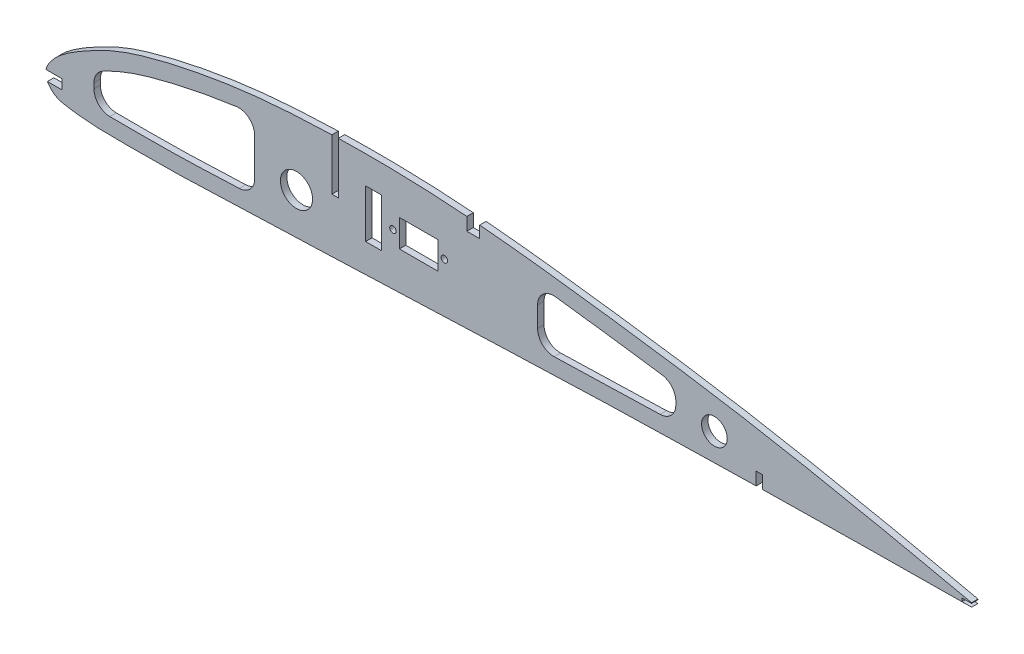
SolidWorks part; units mm, degrees
material "轻木"
ref_plane "前视基准面" through (0, 0, 0) normal (0, 0, 1) x (1, 0, 0)
ref_plane "上视基准面" through (0, 0, 0) normal (0, 1, 0) x (1, 0, 0)
ref_plane "右视基准面" through (0, 0, 0) normal (1, 0, 0) x (0, 0, -1)
other "Configuration Table"
curve "曲线1"
  spline degree 3 poles (300, 0.375, 0) (299.2857, 0.5355, 0) (297.8572, 0.8566, 0) (295.7147, 1.3378, 0) (293.5725, 1.8185, 0) (291.4302, 2.2982, 0) (289.2875, 2.7769, 0) (287.1442, 3.2543, 0) (285.001, 3.7299, 0) (282.8583, 4.2033, 0) (280.7163, 4.6744, 0) (278.5743, 5.1433, 0) (276.432, 5.6099, 0) (274.2889, 6.0741, 0) (272.145, 6.5358, 0) (269.2891, 7.1472, 0) (265.721, 7.9038, 0) (261.4399, 8.8, 0) (257.1573, 9.6847, 0) (252.8725, 10.5577, 0) (248.585, 11.4191, 0) (244.2942, 12.2686, 0) (240.0067, 13.1048, 0) (235.7231, 13.9276, 0) (231.4437, 14.735, 0) (227.1623, 15.5265, 0) (222.8779, 16.3002, 0) (218.5899, 17.0545, 0) (214.2976, 17.7876, 0) (210.0082, 18.4964, 0) (205.7223, 19.1793, 0) (201.441, 19.8388, 0) (197.1575, 20.4787, 0) (192.8717, 21.1016, 0) (188.5834, 21.71, 0) (184.2928, 22.3067, 0) (180.0042, 22.8936, 0) (175.7188, 23.4732, 0) (171.4371, 24.0431, 0) (167.1545, 24.6013, 0) (162.8704, 25.1452, 0) (158.5838, 25.6724, 0) (154.2938, 26.1804, 0) (150.0066, 26.6658, 0) (145.7226, 27.1265, 0) (141.4425, 27.5584, 0) (137.1601, 27.958, 0) (132.875, 28.3213, 0) (128.5869, 28.6439, 0) (124.2953, 28.9218, 0) (120.0053, 29.1506, 0) (115.7177, 29.3264, 0) (111.4337, 29.4514, 0) (107.1488, 29.5275, 0) (102.863, 29.5565, 0) (98.5762, 29.5401, 0) (94.2882, 29.4801, 0) (89.9957, 29.378, 0) (85.6999, 29.236, 0) (81.4026, 29.047, 0) (77.1093, 28.8043, 0) (72.8211, 28.5008, 0) (68.5389, 28.1296, 0) (64.264, 27.6835, 0) (60.7007, 27.2426, 0) (57.8461, 26.8442, 0) (55.696, 26.5216, 0) (53.5496, 26.1773, 0) (51.4067, 25.8115, 0) (49.2673, 25.4247, 0) (47.1314, 25.0171, 0) (44.9882, 24.5868, 0) (42.838, 24.1341, 0) (40.6818, 23.6568, 0) (38.5315, 23.1552, 0) (36.3875, 22.6273, 0) (34.2503, 22.0712, 0) (32.1202, 21.4847, 0) (30.3423, 20.9664, 0) (28.9132, 20.5311, 0) (27.8303, 20.1897, 0) (26.7518, 19.8362, 0) (25.6784, 19.4687, 0) (24.6112, 19.0858, 0) (23.551, 18.6856, 0) (22.4821, 18.2598, 0) (21.4059, 17.8057, 0) (20.3222, 17.3242, 0) (19.2465, 16.8243, 0) (18.1774, 16.3076, 0) (17.1139, 15.7762, 0) (16.0546, 15.2317, 0) (14.9819, 14.6674, 0) (13.8954, 14.0851, 0) (12.7977, 13.4827, 0) (11.7087, 12.8677, 0) (10.6313, 12.2387, 0) (9.5687, 11.5942, 0) (8.5237, 10.9329, 0) (7.6518, 10.3543, 0) (6.9458, 9.8665, 0) (6.3985, 9.4746, 0) (5.8573, 9.0705, 0) (5.3218, 8.651, 0) (4.7913, 8.2128, 0) (4.2653, 7.7527, 0) (3.6165, 7.1497, 0) (2.8604, 6.3846, 0) (2.0362, 5.4343, 0) (1.2959, 4.4252, 0) (0.6772, 3.3675, 0) (0.2189, 2.2697, 0) (-0.0383, 1.1392, 0) (-0.0456, 0.0749, 0) (0.1619, -0.885, 0) (0.4986, -1.7375, 0) (0.9635, -2.5517, 0) (1.5376, -3.3119, 0) (2.2026, -4.0019, 0) (2.94, -4.6051, 0) (3.6355, -5.044, 0) (4.2555, -5.3464, 0) (4.779, -5.5548, 0) (5.3118, -5.728, 0) (5.8521, -5.8723, 0) (6.398, -5.9938, 0) (6.9478, -6.0987, 0) (7.671, -6.2224, 0) (8.5669, -6.3647, 0) (9.636, -6.5177, 0) (10.7063, -6.6545, 0) (11.7778, -6.7754, 0) (12.8506, -6.8809, 0) (13.9246, -6.9713, 0) (14.9978, -7.047, 0) (16.0697, -7.1082, 0) (17.1403, -7.1566, 0) (18.2115, -7.1941, 0) (19.2831, -7.2222, 0) (20.3552, -7.2427, 0) (21.4275, -7.2573, 0) (22.4998, -7.2676, 0) (23.5718, -7.2752, 0) (24.6434, -7.2803, 0) (25.7147, -7.2832, 0) (26.7859, -7.2843, 0) (27.8572, -7.2839, 0) (28.9285, -7.2822, 0) (30.3573, -7.2788, 0) (32.1433, -7.2727, 0) (34.2864, -7.2613, 0) (36.4292, -7.2444, 0) (38.5718, -7.2208, 0) (40.7144, -7.1891, 0) (42.8572, -7.148, 0) (45.0005, -7.0962, 0) (47.1439, -7.0325, 0) (49.2871, -6.9587, 0) (51.4297, -6.8772, 0) (53.572, -6.7902, 0) (55.7143, -6.6999, 0) (57.857, -6.6086, 0) (60.7142, -6.4884, 0) (64.2858, -6.3465, 0) (68.5714, -6.1868, 0) (72.8565, -6.0353, 0) (77.1416, -5.8893, 0) (81.427, -5.7463, 0) (85.7132, -5.6038, 0) (90.0001, -5.4593, 0) (94.287, -5.3101, 0) (98.5731, -5.1566, 0) (102.8583, -4.9992, 0) (107.1431, -4.8383, 0) (111.4281, -4.6742, 0) (115.7138, -4.5074, 0) (120.0001, -4.3383, 0) (124.2865, -4.1673, 0) (128.5722, -3.9953, 0) (132.8572, -3.8233, 0) (137.142, -3.6525, 0) (141.4271, -3.4838, 0) (145.7131, -3.3181, 0) (149.9996, -3.1567, 0) (154.286, -3.0004, 0) (158.5714, -2.8495, 0) (162.8564, -2.7043, 0) (167.1412, -2.5651, 0) (171.4266, -2.4321, 0) (175.7128, -2.3056, 0) (179.9996, -2.1858, 0) (184.2862, -2.0731, 0) (188.5719, -1.9664, 0) (192.857, -1.8646, 0) (197.1419, -1.7668, 0) (201.4272, -1.6719, 0) (205.7132, -1.5788, 0) (209.9999, -1.4865, 0) (214.2864, -1.3941, 0) (218.5722, -1.3027, 0) (222.8572, -1.2136, 0) (227.142, -1.128, 0) (231.4272, -1.0471, 0) (235.7132, -0.9723, 0) (239.9998, -0.9046, 0) (244.2864, -0.8454, 0) (248.5722, -0.7928, 0) (252.8573, -0.7451, 0) (257.1422, -0.7003, 0) (261.4274, -0.6568, 0) (265.7134, -0.6127, 0) (269.2855, -0.574, 0) (272.1433, -0.5408, 0) (274.2862, -0.5157, 0) (276.4287, -0.4908, 0) (278.5712, -0.4671, 0) (280.7137, -0.4452, 0) (282.8567, -0.4258, 0) (285, -0.4096, 0) (287.1432, -0.3973, 0) (289.2862, -0.3884, 0) (291.4287, -0.3824, 0) (293.5711, -0.3786, 0) (295.7137, -0.3765, 0) (297.8567, -0.3754, 0) (299.2855, -0.3751, 0) (300, -0.375, 0) knots 0 0 0 0 0.003574 0.007146 0.010718 0.01429 0.017862 0.021434 0.025008 0.028577 0.032145 0.035713 0.03928 0.042847 0.046415 0.049985 0.057103 0.064219 0.071333 0.078448 0.085563 0.092679 0.099797 0.106885 0.11397 0.121053 0.128137 0.13522 0.142305 0.149391 0.15644 0.163488 0.170534 0.17758 0.184627 0.191675 0.198725 0.205755 0.212782 0.219809 0.226834 0.233861 0.240889 0.24792 0.254921 0.26192 0.268917 0.275914 0.28291 0.289907 0.296905 0.303879 0.310852 0.317824 0.324796 0.331771 0.338748 0.345728 0.352728 0.359727 0.366723 0.373717 0.380709 0.387701 0.394695 0.398233 0.40177 0.405307 0.408843 0.41238 0.415918 0.419457 0.42305 0.426643 0.430235 0.433828 0.43742 0.441014 0.444611 0.446459 0.448306 0.450153 0.451999 0.453844 0.455687 0.45753 0.459459 0.461388 0.463318 0.465249 0.467183 0.469121 0.471062 0.4731 0.475138 0.477173 0.479204 0.481227 0.483239 0.48524 0.486334 0.487428 0.488525 0.48963 0.490748 0.491883 0.493041 0.495071 0.497131 0.499176 0.501171 0.503098 0.50496 0.506796 0.508242 0.509728 0.511253 0.512804 0.514366 0.515919 0.517444 0.518368 0.519283 0.520192 0.521101 0.522011 0.522922 0.523833 0.525592 0.527349 0.529104 0.530859 0.532612 0.534366 0.53612 0.537863 0.539607 0.54135 0.543094 0.544839 0.546584 0.548329 0.550073 0.551817 0.55356 0.555302 0.557045 0.558788 0.560532 0.564019 0.567506 0.570992 0.574478 0.577965 0.581452 0.584939 0.588429 0.591918 0.595406 0.598895 0.602383 0.605872 0.609363 0.616342 0.623319 0.630295 0.637271 0.644247 0.651224 0.658203 0.665183 0.672161 0.679137 0.686114 0.69309 0.700068 0.707048 0.714028 0.721006 0.727983 0.73496 0.741937 0.748915 0.755896 0.762874 0.769851 0.776826 0.783801 0.790777 0.797753 0.804732 0.811709 0.818683 0.825657 0.83263 0.839604 0.846578 0.853555 0.860532 0.867506 0.874479 0.881452 0.888424 0.895399 0.902375 0.90935 0.916324 0.923296 0.930267 0.937239 0.944213 0.951188 0.954676 0.958163 0.961649 0.965135 0.96862 0.972107 0.975595 0.979082 0.982569 0.986054 0.98954 0.993026 0.996512 1 1 1 1
curve "曲线2"
  spline degree 3 poles (299.6892, 0.0825, 0) (300.1498, -0.0478, 0) (299.7114, 0.1074, 0) (299.5104, 0.1872, 0) (299.2477, 0.2871, 0) (298.8504, 0.4413, 0) (298.294, 0.6613, 0) (297.5919, 0.9463, 0) (296.8903, 1.2362, 0) (296.0644, 1.581, 0) (295.1136, 1.9799, 0) (294.0373, 2.431, 0) (292.9597, 2.8788, 0) (291.7683, 3.3665, 0) (290.4608, 3.8877, 0) (289.0365, 4.4399, 0) (287.6073, 4.9796, 0) (286.0635, 5.5484, 0) (284.4048, 6.1444, 0) (282.6311, 6.7664, 0) (280.8534, 7.377, 0) (278.9651, 8.0149, 0) (276.9667, 8.6805, 0) (274.8582, 9.373, 0) (272.7471, 10.0574, 0) (270.5382, 10.7652, 0) (268.2318, 11.4959, 0) (265.8278, 12.2485, 0) (263.4214, 12.9932, 0) (260.9293, 13.7558, 0) (258.3517, 14.5354, 0) (255.6885, 15.3308, 0) (253.0225, 16.1168, 0) (250.2835, 16.9138, 0) (247.4714, 17.7205, 0) (244.5864, 18.536, 0) (241.6982, 19.3402, 0) (238.749, 20.1489, 0) (235.7391, 20.9612, 0) (232.6684, 21.7757, 0) (229.594, 22.5763, 0) (226.4711, 23.374, 0) (223.2997, 24.1675, 0) (220.08, 24.9553, 0) (216.8561, 25.726, 0) (213.5945, 26.4871, 0) (210.2953, 27.2373, 0) (206.9588, 27.975, 0) (203.6178, 28.6919, 0) (200.2497, 29.3918, 0) (196.8549, 30.0732, 0) (193.4336, 30.7349, 0) (190.0077, 31.3718, 0) (186.5618, 31.9862, 0) (183.0963, 32.577, 0) (179.6117, 33.1436, 0) (176.1229, 33.6833, 0) (172.6234, 34.197, 0) (169.1136, 34.6844, 0) (165.5943, 35.1447, 0) (162.0713, 35.5767, 0) (158.5465, 35.9798, 0) (155.0205, 36.3535, 0) (151.4939, 36.6979, 0) (147.9646, 37.0129, 0) (144.4431, 37.2978, 0) (140.9302, 37.5529, 0) (137.4264, 37.7777, 0) (133.9208, 37.9727, 0) (130.4332, 38.1365, 0) (126.9642, 38.269, 0) (123.5147, 38.3706, 0) (120.0643, 38.4412, 0) (116.6408, 38.4803, 0) (113.2449, 38.4881, 0) (109.8772, 38.4649, 0) (106.5099, 38.4098, 0) (103.1795, 38.3231, 0) (99.8867, 38.2053, 0) (96.6323, 38.0567, 0) (93.3796, 37.8749, 0) (90.1728, 37.6618, 0) (87.0127, 37.4182, 0) (83.9, 37.1447, 0) (80.7905, 36.8368, 0) (77.7347, 36.4989, 0) (74.7332, 36.1323, 0) (71.7867, 35.7377, 0) (68.8452, 35.3075, 0) (65.9638, 34.8492, 0) (63.1431, 34.3642, 0) (60.3838, 33.8535, 0) (57.6314, 33.3063, 0) (54.9457, 32.7337, 0) (52.327, 32.1376, 0) (49.7758, 31.5197, 0) (47.2337, 30.8655, 0) (44.763, 30.1905, 0) (42.364, 29.4973, 0) (40.0371, 28.7872, 0) (37.7217, 28.0406, 0) (35.4836, 27.2778, 0) (33.323, 26.5013, 0) (31.2399, 25.7132, 0) (29.1709, 24.8888, 0) (27.1829, 24.0541, 0) (25.2756, 23.212, 0) (23.4491, 22.3647, 0) (21.6401, 21.481, 0) (19.9159, 20.5922, 0) (18.2759, 19.7016, 0) (16.7198, 18.8121, 0) (15.1846, 17.8866, 0) (13.7354, 16.9627, 0) (12.3708, 16.045, 0) (11.0909, 15.1361, 0) (9.8373, 14.192, 0) (8.6721, 13.2572, 0) (7.5935, 12.336, 0) (6.5993, 11.4319, 0) (5.6356, 10.4933, 0) (4.7571, 9.5716, 0) (3.961, 8.6731, 0) (3.2484, 7.802, 0) (2.5791, 6.9017, 0) (2.0018, 6.0303, 0) (1.5119, 5.1928, 0) (1.098, 4.3932, 0) (0.723, 3.565, 0) (0.4148, 2.7772, 0) (0.1635, 2.0409, 0) (-0.0076, 1.362, 0) (-0.0857, 0.6761, 0) (-0.0312, 0.0318, 0) (0.1575, -0.5446, 0) (0.4284, -1.0495, 0) (0.7766, -1.5095, 0) (1.2499, -1.9767, 0) (1.8739, -2.4002, 0) (2.6419, -2.7457, 0) (3.4475, -3.0028, 0) (4.3968, -3.243, 0) (5.4726, -3.4987, 0) (6.6732, -3.7581, 0) (7.8724, -3.9885, 0) (9.2039, -4.2095, 0) (10.6736, -4.4054, 0) (12.2821, -4.571, 0) (13.8972, -4.6995, 0) (15.6445, -4.8094, 0) (17.5211, -4.9053, 0) (19.5261, -4.9826, 0) (21.5305, -5.0368, 0) (23.661, -5.0721, 0) (25.9181, -5.0854, 0) (28.3014, -5.0749, 0) (30.6852, -5.0437, 0) (33.1885, -4.993, 0) (35.8107, -4.9237, 0) (38.5514, -4.8343, 0) (41.2914, -4.7299, 0) (44.1429, -4.6075, 0) (47.1057, -4.467, 0) (50.1792, -4.3077, 0) (53.2522, -4.1367, 0) (56.4269, -3.9498, 0) (59.7026, -3.7473, 0) (63.0791, -3.5293, 0) (66.4551, -3.3033, 0) (69.9209, -3.0645, 0) (73.4761, -2.8134, 0) (77.1202, -2.5502, 0) (80.764, -2.2824, 0) (84.4846, -2.0051, 0) (88.2815, -1.7191, 0) (92.1543, -1.4245, 0) (96.027, -1.128, 0) (99.9621, -0.8252, 0) (103.9592, -0.5167, 0) (108.0179, -0.2032, 0) (112.0767, 0.1098, 0) (116.1823, 0.4251, 0) (120.3344, 0.742, 0) (124.5324, 1.0596, 0) (128.7308, 1.3739, 0) (132.9595, 1.6861, 0) (137.2181, 1.9957, 0) (141.506, 2.3018, 0) (145.7945, 2.6016, 0) (150.096, 2.8954, 0) (154.41, 3.1825, 0) (158.7362, 3.4618, 0) (163.063, 3.7316, 0) (167.3848, 3.9907, 0) (171.7011, 4.2382, 0) (176.0115, 4.4733, 0) (180.3226, 4.6957, 0) (184.6083, 4.9033, 0) (188.8679, 5.0957, 0) (193.1011, 5.2721, 0) (197.335, 5.4325, 0) (201.5222, 5.5742, 0) (205.6623, 5.6969, 0) (209.7546, 5.8004, 0) (213.8473, 5.8854, 0) (217.8716, 5.9498, 0) (221.8268, 5.9942, 0) (225.7124, 6.0188, 0) (229.598, 6.0233, 0) (233.3935, 6.0071, 0) (237.0983, 5.971, 0) (240.7119, 5.9157, 0) (244.325, 5.8393, 0) (247.8275, 5.7436, 0) (251.2186, 5.6301, 0) (254.498, 5.5, 0) (257.7765, 5.3484, 0) (260.9253, 5.1809, 0) (263.9441, 4.9996, 0) (266.8324, 4.8058, 0) (269.7191, 4.5899, 0) (272.4587, 4.362, 0) (275.0509, 4.1249, 0) (277.4951, 3.8799, 0) (279.9368, 3.6105, 0) (282.2113, 3.3338, 0) (284.3185, 3.0537, 0) (286.2585, 2.7745, 0) (288.195, 2.4723, 0) (289.9467, 2.1761, 0) (291.5141, 1.8919, 0) (292.8979, 1.6262, 0) (294.2788, 1.3456, 0) (295.4709, 1.0894, 0) (296.4751, 0.8638, 0) (297.2928, 0.6738, 0) (298.1076, 0.4784, 0) (298.7442, 0.3204, 0) (299.1896, 0.208, 0) (299.4728, 0.1348, 0) (299.6892, 0.0825, 0) (300.1498, -0.0478, 0) (299.7114, 0.1074, 0) knots -0.001345 -0.000897 -0.000449 0 0.000432 0.000863 0.001295 0.001726 0.002951 0.004176 0.0054 0.006625 0.008509 0.010392 0.012274 0.014158 0.016623 0.019088 0.021553 0.024019 0.027053 0.030085 0.033118 0.036152 0.039734 0.043315 0.046896 0.050478 0.054544 0.058608 0.062672 0.066738 0.071224 0.075709 0.080193 0.084679 0.089518 0.094356 0.099193 0.104032 0.10916 0.114286 0.119411 0.124539 0.129889 0.135237 0.140585 0.145936 0.151451 0.156964 0.162478 0.167993 0.173617 0.17924 0.184862 0.190486 0.196184 0.20188 0.207576 0.213274 0.219003 0.22473 0.230457 0.236185 0.241905 0.247622 0.253339 0.259058 0.264725 0.270389 0.276054 0.281721 0.287291 0.29286 0.298428 0.303998 0.309434 0.314867 0.320301 0.325737 0.330995 0.336251 0.341507 0.346766 0.351809 0.356851 0.361892 0.366936 0.371734 0.37653 0.381327 0.386125 0.390654 0.395182 0.399709 0.404238 0.408475 0.41271 0.416945 0.421182 0.425109 0.429034 0.432959 0.436885 0.44048 0.444073 0.447666 0.451261 0.454511 0.457759 0.461007 0.464256 0.467149 0.470041 0.472933 0.475826 0.47836 0.480893 0.483425 0.485956 0.488123 0.490291 0.49246 0.494634 0.496453 0.49827 0.500081 0.501882 0.503328 0.504776 0.506239 0.507727 0.50887 0.510003 0.51111 0.512198 0.513104 0.514027 0.514959 0.515886 0.517235 0.518584 0.51995 0.521324 0.523324 0.525303 0.52727 0.529235 0.531836 0.534446 0.537062 0.539679 0.542921 0.546158 0.549393 0.552628 0.556473 0.560319 0.564166 0.568014 0.57244 0.576864 0.581288 0.585714 0.590681 0.595647 0.600613 0.605581 0.611042 0.616501 0.62196 0.627422 0.633319 0.639214 0.645109 0.651006 0.657275 0.663542 0.669809 0.676078 0.682648 0.689216 0.695784 0.702355 0.70915 0.715943 0.722736 0.729531 0.73647 0.743406 0.750342 0.757281 0.764278 0.771273 0.778268 0.785265 0.792232 0.799197 0.806162 0.81313 0.819969 0.826805 0.833641 0.840479 0.847087 0.853692 0.860297 0.866904 0.873175 0.879445 0.885714 0.891986 0.897819 0.90365 0.909481 0.915314 0.920611 0.925907 0.931202 0.936499 0.941172 0.945842 0.950513 0.955185 0.95915 0.963114 0.967077 0.971042 0.974206 0.977368 0.98053 0.983693 0.985968 0.988241 0.990515 0.992789 0.994144 0.995498 0.996852 0.998206 0.998655 0.999103 0.999551 1 1.000432 1.000863 1.001295 periodic
sketch "草图1" plane through (0, 0, 0) normal (0, 0, 1) x (1, 0, 0)
  line L1 (290, 2.6177) -> (290, -0.3866)
  line L2 (289, 1.8162) -> (289, 0.6101)
  line L3 (0, 0) -> (0, 30) construction
  line L4 (-6, -1.5) -> (6, -1.5)
  line L5 (-6, -1.5) -> (-6, 1.5)
  line L6 (-6, 1.5) -> (6, 1.5)
  line L7 (6, -1.5) -> (6, 1.5)
  line L8 (-6, -1.5) -> (6, 1.5) construction
  line L9 (-6, 1.5) -> (6, -1.5) construction
  line L10 (-1000, 0) -> (49000, 0) construction
  line L11 (90, 29.3715) -> (92, 29.3715)
  line L12 (90, 29.3715) -> (90, 12.3715)
  line L13 (90, 12.3715) -> (92, 12.3715)
  line L14 (92, 29.3715) -> (92, 12.3715)
  line L16 (222, -1.2317) -> (224, -1.2317)
  line L17 (222, -1.2317) -> (222, 3.7683)
  line L18 (222, 3.7683) -> (224, 3.7683)
  line L19 (224, -1.2317) -> (224, 3.7683)
  line L20 (289, 0.6101) -> (286, 0.6101)
  line L21 (289, 0.6101) -> (289, 1.6101)
  line L22 (289, 1.6101) -> (286, 1.6101)
  line L23 (286, 0.6101) -> (286, 1.6101)
  circle A0 centre (79, 8) radius 5
  circle A1 centre (209, 8) radius 4
  spline S0 degree 3 poles (1772.1833, 2527.0993) (871.6721, -135.2205) (584.8189, -63.6019) (295.7147, 1.3378) (293.5725, 1.8185) (291.4302, 2.2982) (289.2875, 2.7769) (287.1442, 3.2543) (285.001, 3.7299) (282.8583, 4.2033) (280.7163, 4.6744) (278.5743, 5.1433) (276.432, 5.6099) (274.2889, 6.0741) (272.145, 6.5358) (269.2891, 7.1472) (265.721, 7.9038) (261.4399, 8.8) (257.1573, 9.6847) (252.8725, 10.5577) (248.585, 11.4191) (244.2942, 12.2686) (240.0067, 13.1048) (234.2978, 14.2013) (228.5907, 15.2685) (222.8779, 16.3002) (218.5899, 17.0545) (214.2976, 17.7876) (210.0082, 18.4964) (205.7223, 19.1793) (201.441, 19.8388) (197.1575, 20.4787) (192.8717, 21.1016) (188.5834, 21.71) (184.2928, 22.3067) (180.0042, 22.8936) (175.7188, 23.4732) (171.4371, 24.0431) (167.1545, 24.6013) (162.8704, 25.1452) (158.5838, 25.6724) (154.2938, 26.1804) (150.0066, 26.6658) (145.7226, 27.1265) (141.4425, 27.5584) (137.1601, 27.958) (132.875, 28.3213) (128.5869, 28.6439) (124.2953, 28.9218) (120.0053, 29.1506) (115.7177, 29.3264) (111.4337, 29.4514) (107.1488, 29.5275) (102.863, 29.5565) (98.5762, 29.5401) (94.2882, 29.4801) (89.9957, 29.378) (85.6999, 29.236) (81.4026, 29.047) (77.1093, 28.8043) (72.8211, 28.5008) (68.5389, 28.1296) (64.264, 27.6835) (60.7007, 27.2426) (57.1284, 26.744) (53.5478, 26.188) (49.9791, 25.5605) (47.1314, 25.0171) (44.9882, 24.5868) (42.838, 24.1341) (40.6818, 23.6568) (38.5315, 23.1552) (36.3875, 22.6273) (34.2503, 22.0712) (32.1202, 21.4847) (30.3423, 20.9664) (28.9132, 20.5311) (27.8303, 20.1897) (26.7518, 19.8362) (25.6784, 19.4687) (24.6112, 19.0858) (23.551, 18.6856) (22.4821, 18.2598) (21.4059, 17.8057) (20.3222, 17.3242) (19.2465, 16.8243) (18.1774, 16.3076) (17.1139, 15.7762) (16.0546, 15.2317) (14.9819, 14.6674) (13.8954, 14.0851) (12.7977, 13.4827) (11.7087, 12.8677) (10.6313, 12.2387) (9.5687, 11.5942) (8.5237, 10.9329) (7.6518, 10.3543) (6.9458, 9.8665) (6.3985, 9.4746) (5.8573, 9.0705) (5.3218, 8.651) (4.7913, 8.2128) (4.2653, 7.7527) (3.6165, 7.1497) (2.8604, 6.3846) (2.0362, 5.4343) (1.2959, 4.4252) (0.6772, 3.3675) (0.2189, 2.2697) (-0.0383, 1.1392) (-0.0456, 0.0749) (0.1619, -0.885) (0.4986, -1.7375) (0.9635, -2.5517) (1.5376, -3.3119) (2.2026, -4.0019) (2.94, -4.6051) (3.6355, -5.044) (4.2555, -5.3464) (4.779, -5.5548) (5.3118, -5.728) (5.8521, -5.8723) (6.398, -5.9938) (6.9478, -6.0987) (7.671, -6.2224) (8.5669, -6.3647) (9.9918, -6.5686) (11.4199, -6.7402) (12.8506, -6.8809) (13.9246, -6.9713) (14.9978, -7.047) (16.0697, -7.1082) (17.1403, -7.1566) (18.2115, -7.1941) (19.2831, -7.2222) (20.3552, -7.2427) (21.4275, -7.2573) (22.4998, -7.2676) (23.5718, -7.2752) (24.6434, -7.2803) (25.7147, -7.2832) (27.143, -7.2847) (28.5715, -7.283) (30.3573, -7.2788) (32.1433, -7.2727) (34.2864, -7.2613) (36.4292, -7.2444) (38.5718, -7.2208) (40.7144, -7.1891) (42.8572, -7.148) (45.0005, -7.0962) (47.1439, -7.0325) (49.2871, -6.9587) (51.4297, -6.8772) (54.2862, -6.7612) (57.1429, -6.6386) (60.7142, -6.4884) (64.2858, -6.3465) (69.9995, -6.1336) (75.7132, -5.9369) (81.427, -5.7463) (85.7132, -5.6038) (90.0001, -5.4593) (94.287, -5.3101) (98.5731, -5.1566) (102.8583, -4.9992) (108.5717, -4.7846) (114.2856, -4.5638) (120.0001, -4.3383) (124.2865, -4.1673) (128.5722, -3.9953) (132.8572, -3.8233) (137.142, -3.6525) (141.4271, -3.4838) (145.7131, -3.3181) (149.9996, -3.1567) (154.286, -3.0004) (158.5714, -2.8495) (164.2846, -2.656) (171.4272, -2.4288) (179.9991, -2.1823) (187.1429, -2.0003) (192.857, -1.8646) (197.1419, -1.7668) (201.4272, -1.6719) (205.7132, -1.5788) (209.9999, -1.4865) (214.2864, -1.3941) (218.5722, -1.3027) (222.8572, -1.2136) (227.142, -1.128) (231.4272, -1.0471) (235.7132, -0.9723) (239.9998, -0.9046) (244.2864, -0.8454) (248.5722, -0.7928) (252.8573, -0.7451) (258.5708, -0.6854) (264.285, -0.6282) (269.2855, -0.574) (272.1433, -0.5408) (274.2862, -0.5157) (276.4287, -0.4908) (278.5712, -0.4671) (280.7137, -0.4452) (282.8567, -0.4258) (285, -0.4096) (287.1432, -0.3973) (289.2862, -0.3884) (291.4287, -0.3824) (293.5711, -0.3786) (295.7137, -0.3765) (521.6922, -0.2702) (746.959, -9.4705) (970.7683, 2878.2814) knots -1.435568 -1.435568 -1.435568 -1.435568 0.003574 0.007146 0.010718 0.01429 0.017862 0.021434 0.025008 0.028577 0.032145 0.035713 0.03928 0.042847 0.046415 0.049985 0.057103 0.064219 0.071333 0.078448 0.085563 0.092679 0.099797 0.106885 0.121053 0.128137 0.13522 0.142305 0.149391 0.15644 0.163488 0.170534 0.17758 0.184627 0.191675 0.198725 0.205755 0.212782 0.219809 0.226834 0.233861 0.240889 0.24792 0.254921 0.26192 0.268917 0.275914 0.28291 0.289907 0.296905 0.303879 0.310852 0.317824 0.324796 0.331771 0.338748 0.345728 0.352728 0.359727 0.366723 0.373717 0.380709 0.387701 0.394695 0.398233 0.405307 0.41238 0.415918 0.419457 0.42305 0.426643 0.430235 0.433828 0.43742 0.441014 0.444611 0.446459 0.448306 0.450153 0.451999 0.453844 0.455687 0.45753 0.459459 0.461388 0.463318 0.465249 0.467183 0.469121 0.471062 0.4731 0.475138 0.477173 0.479204 0.481227 0.483239 0.48524 0.486334 0.487428 0.488525 0.48963 0.490748 0.491883 0.493041 0.495071 0.497131 0.499176 0.501171 0.503098 0.50496 0.506796 0.508242 0.509728 0.511253 0.512804 0.514366 0.515919 0.517444 0.518368 0.519283 0.520192 0.521101 0.522011 0.522922 0.523833 0.525592 0.527349 0.530859 0.532612 0.534366 0.53612 0.537863 0.539607 0.54135 0.543094 0.544839 0.546584 0.548329 0.550073 0.551817 0.55356 0.555302 0.558788 0.560532 0.564019 0.567506 0.570992 0.574478 0.577965 0.581452 0.584939 0.588429 0.591918 0.595406 0.598895 0.605872 0.609363 0.616342 0.623319 0.637271 0.644247 0.651224 0.658203 0.665183 0.672161 0.679137 0.686114 0.700068 0.707048 0.714028 0.721006 0.727983 0.73496 0.741937 0.748915 0.755896 0.762874 0.769851 0.776826 0.790777 0.804732 0.818683 0.825657 0.83263 0.839604 0.846578 0.853555 0.860532 0.867506 0.874479 0.881452 0.888424 0.895399 0.902375 0.90935 0.916324 0.923296 0.930267 0.944213 0.951188 0.954676 0.958163 0.961649 0.965135 0.96862 0.972107 0.975595 0.979082 0.982569 0.986054 0.98954 0.993026 0.996512 2.092547 2.092547 2.092547 2.092547 only from (300, 0.375) to (300, -0.375) construction
  spline S1 degree 3 poles (290, 2.6177) (289.0482, 2.8302) (287.3817, 3.2016) (285.001, 3.7299) (282.8583, 4.2033) (280.7163, 4.6744) (278.5743, 5.1433) (276.432, 5.6099) (274.2889, 6.0741) (272.145, 6.5358) (269.2891, 7.1472) (265.721, 7.9038) (261.4399, 8.8) (257.1573, 9.6847) (252.8725, 10.5577) (248.585, 11.4191) (244.2942, 12.2686) (240.0067, 13.1048) (234.2978, 14.2013) (228.5907, 15.2685) (222.8779, 16.3002) (218.5899, 17.0545) (214.2976, 17.7876) (210.0082, 18.4964) (205.7223, 19.1793) (201.441, 19.8388) (197.1575, 20.4787) (192.8717, 21.1016) (188.5834, 21.71) (184.2928, 22.3067) (180.0042, 22.8936) (175.7188, 23.4732) (171.4371, 24.0431) (167.1545, 24.6013) (162.8704, 25.1452) (158.5838, 25.6724) (154.2938, 26.1804) (150.0066, 26.6658) (145.7226, 27.1265) (141.4425, 27.5584) (137.1601, 27.958) (132.875, 28.3213) (128.5869, 28.6439) (124.2953, 28.9218) (120.0053, 29.1506) (115.7177, 29.3264) (111.4337, 29.4514) (107.1488, 29.5275) (102.863, 29.5565) (98.5762, 29.5401) (94.2882, 29.4801) (89.9957, 29.378) (85.6999, 29.236) (81.4026, 29.047) (77.1093, 28.8043) (72.8211, 28.5008) (68.5389, 28.1296) (64.264, 27.6835) (60.7007, 27.2426) (57.1284, 26.744) (53.5478, 26.188) (49.9791, 25.5605) (47.1314, 25.0171) (44.9882, 24.5868) (42.838, 24.1341) (40.6818, 23.6568) (38.5315, 23.1552) (36.3875, 22.6273) (34.2503, 22.0712) (32.1202, 21.4847) (30.3423, 20.9664) (28.9132, 20.5311) (27.8303, 20.1897) (26.7518, 19.8362) (25.6784, 19.4687) (24.6112, 19.0858) (23.551, 18.6856) (22.4821, 18.2598) (21.4059, 17.8057) (20.3222, 17.3242) (19.2465, 16.8243) (18.1774, 16.3076) (17.1139, 15.7762) (16.0546, 15.2317) (14.9819, 14.6674) (13.8954, 14.0851) (12.7977, 13.4827) (11.7087, 12.8677) (10.6313, 12.2387) (9.5687, 11.5942) (8.5237, 10.9329) (7.6518, 10.3543) (6.9458, 9.8665) (6.3985, 9.4746) (5.8573, 9.0705) (5.3218, 8.651) (4.7913, 8.2128) (4.2653, 7.7527) (3.6165, 7.1497) (2.8604, 6.3846) (2.0362, 5.4343) (1.2959, 4.4252) (0.6772, 3.3675) (0.2189, 2.2697) (-0.0383, 1.1392) (-0.0456, 0.0749) (0.1619, -0.885) (0.4986, -1.7375) (0.9635, -2.5517) (1.5376, -3.3119) (2.2026, -4.0019) (2.94, -4.6051) (3.6355, -5.044) (4.2555, -5.3464) (4.779, -5.5548) (5.3118, -5.728) (5.8521, -5.8723) (6.398, -5.9938) (6.9478, -6.0987) (7.671, -6.2224) (8.5669, -6.3647) (9.9918, -6.5686) (11.4199, -6.7402) (12.8506, -6.8809) (13.9246, -6.9713) (14.9978, -7.047) (16.0697, -7.1082) (17.1403, -7.1566) (18.2115, -7.1941) (19.2831, -7.2222) (20.3552, -7.2427) (21.4275, -7.2573) (22.4998, -7.2676) (23.5718, -7.2752) (24.6434, -7.2803) (25.7147, -7.2832) (27.143, -7.2847) (28.5715, -7.283) (30.3573, -7.2788) (32.1433, -7.2727) (34.2864, -7.2613) (36.4292, -7.2444) (38.5718, -7.2208) (40.7144, -7.1891) (42.8572, -7.148) (45.0005, -7.0962) (47.1439, -7.0325) (49.2871, -6.9587) (51.4297, -6.8772) (54.2862, -6.7612) (57.1429, -6.6386) (60.7142, -6.4884) (64.2858, -6.3465) (69.9995, -6.1336) (75.7132, -5.9369) (81.427, -5.7463) (85.7132, -5.6038) (90.0001, -5.4593) (94.287, -5.3101) (98.5731, -5.1566) (102.8583, -4.9992) (108.5717, -4.7846) (114.2856, -4.5638) (120.0001, -4.3383) (124.2865, -4.1673) (128.5722, -3.9953) (132.8572, -3.8233) (137.142, -3.6525) (141.4271, -3.4838) (145.7131, -3.3181) (149.9996, -3.1567) (154.286, -3.0004) (158.5714, -2.8495) (164.2846, -2.656) (171.4272, -2.4288) (179.9991, -2.1823) (187.1429, -2.0003) (192.857, -1.8646) (197.1419, -1.7668) (201.4272, -1.6719) (205.7132, -1.5788) (209.9999, -1.4865) (214.2864, -1.3941) (218.5722, -1.3027) (222.8572, -1.2136) (227.142, -1.128) (231.4272, -1.0471) (235.7132, -0.9723) (239.9998, -0.9046) (244.2864, -0.8454) (248.5722, -0.7928) (252.8573, -0.7451) (258.5708, -0.6854) (264.285, -0.6282) (269.2855, -0.574) (272.1433, -0.5408) (274.2862, -0.5157) (276.4287, -0.4908) (278.5712, -0.4671) (280.7137, -0.4452) (282.8567, -0.4258) (285, -0.4096) (287.1432, -0.3973) (288.8099, -0.3904) (289.7621, -0.3873) (290, -0.3866) knots 0.016674 0.016674 0.016674 0.016674 0.021434 0.025008 0.028577 0.032145 0.035713 0.03928 0.042847 0.046415 0.049985 0.057103 0.064219 0.071333 0.078448 0.085563 0.092679 0.099797 0.106885 0.121053 0.128137 0.13522 0.142305 0.149391 0.15644 0.163488 0.170534 0.17758 0.184627 0.191675 0.198725 0.205755 0.212782 0.219809 0.226834 0.233861 0.240889 0.24792 0.254921 0.26192 0.268917 0.275914 0.28291 0.289907 0.296905 0.303879 0.310852 0.317824 0.324796 0.331771 0.338748 0.345728 0.352728 0.359727 0.366723 0.373717 0.380709 0.387701 0.394695 0.398233 0.405307 0.41238 0.415918 0.419457 0.42305 0.426643 0.430235 0.433828 0.43742 0.441014 0.444611 0.446459 0.448306 0.450153 0.451999 0.453844 0.455687 0.45753 0.459459 0.461388 0.463318 0.465249 0.467183 0.469121 0.471062 0.4731 0.475138 0.477173 0.479204 0.481227 0.483239 0.48524 0.486334 0.487428 0.488525 0.48963 0.490748 0.491883 0.493041 0.495071 0.497131 0.499176 0.501171 0.503098 0.50496 0.506796 0.508242 0.509728 0.511253 0.512804 0.514366 0.515919 0.517444 0.518368 0.519283 0.520192 0.521101 0.522011 0.522922 0.523833 0.525592 0.527349 0.530859 0.532612 0.534366 0.53612 0.537863 0.539607 0.54135 0.543094 0.544839 0.546584 0.548329 0.550073 0.551817 0.55356 0.555302 0.558788 0.560532 0.564019 0.567506 0.570992 0.574478 0.577965 0.581452 0.584939 0.588429 0.591918 0.595406 0.598895 0.605872 0.609363 0.616342 0.623319 0.637271 0.644247 0.651224 0.658203 0.665183 0.672161 0.679137 0.686114 0.700068 0.707048 0.714028 0.721006 0.727983 0.73496 0.741937 0.748915 0.755896 0.762874 0.769851 0.776826 0.790777 0.804732 0.818683 0.825657 0.83263 0.839604 0.846578 0.853555 0.860532 0.867506 0.874479 0.881452 0.888424 0.895399 0.902375 0.90935 0.916324 0.923296 0.930267 0.944213 0.951188 0.954676 0.958163 0.961649 0.965135 0.96862 0.972107 0.975595 0.979082 0.982569 0.98373 0.98373 0.98373 0.98373
  spline S2 degree 1 poles (289, 1.8162) (289, 0.6101) knots 0 0 1 1 construction
  spline S3 degree 3 poles (289, 1.8162) (276.9573, 4.5023) (258.8616, 8.3976) (234.6482, 13.1528) (216.4485, 16.4789) (198.1829, 19.3716) (179.8506, 21.9241) (161.5032, 24.3586) (143.1279, 26.4732) (124.7122, 28.0438) (106.2546, 28.676) (87.7718, 28.43) (72.4033, 27.5865) (60.1859, 26.2263) (51.081, 24.7981) (42.0339, 23.0001) (34.582, 21.1749) (28.6974, 19.4456) (24.362, 17.9834) (20.1748, 16.2079) (16.0789, 14.1399) (12.0403, 11.9468) (8.1401, 9.5604) (5.1537, 7.3164) (3.1001, 5.2006) (1.8138, 3.4707) (0.9689, 1.5796) (0.9059, -0.2656) (1.7459, -2.0716) (3.1431, -3.6011) (4.8543, -4.6194) (6.9276, -5.1056) (9.209, -5.4548) (12.22, -5.8429) (16.0201, -6.1427) (20.6095, -6.2611) (25.2315, -6.2869) (31.3974, -6.2803) (39.1073, -6.2407) (48.3368, -6.0221) (57.5799, -5.613) (66.8407, -5.2429) (76.0966, -4.9217) (88.436, -4.516) (103.8531, -3.9731) (122.3546, -3.2481) (140.8578, -2.4955) (159.3685, -1.8041) (177.8842, -1.2225) (196.4034, -0.7749) (214.9166, -0.3802) (233.434, 0.0126) (251.9612, 0.2567) (270.4719, 0.4292) (282.8248, 0.5874) (289, 0.6101) knots 0.017978 0.017978 0.017978 0.017978 0.078237 0.108366 0.138495 0.168624 0.198753 0.228882 0.259011 0.28914 0.319269 0.349398 0.379527 0.394592 0.409656 0.424721 0.439785 0.447318 0.45485 0.462382 0.469915 0.477447 0.484979 0.492511 0.496277 0.500044 0.50381 0.507576 0.511342 0.515108 0.518874 0.52264 0.526407 0.530173 0.537705 0.545237 0.552769 0.560302 0.575366 0.590431 0.605495 0.62056 0.635624 0.650689 0.680818 0.710947 0.741076 0.771205 0.801334 0.831463 0.861593 0.891722 0.921851 0.95198 0.982109 0.982109 0.982109 0.982109
  point P8 (0, 0)
  dimension "D9" = 10
  dimension "D10" = 8
  dimension "D1" = 290
  dimension "D2" = 1
  dimension "D3" = 12
  dimension "D4" = 3
  dimension "D5" = 30
  dimension "D6" = 2
  dimension "D7" = 17
  dimension "D8" = 90
  dimension "D11" = 130
  dimension "D12" = 11
  dimension "D13" = 8
  dimension "D14" = 5
  dimension "D15" = 2
  dimension "D16" = 130
  dimension "D17" = 1
  dimension "D18" = 3
extrude "凸台-拉伸1" add sketch "草图1" along normal blind 2 contours L2 S3 | S1 L1
sketch "草图3" plane through (0, 0, 0) normal (0, 0, 1) x (1, 0, 0)
  line L5 (100.5, 4.8715) -> (105.5, 4.8715) construction
  line L6 (90, 12.3715) -> (92, 12.3715) construction
  line L7 (92, 28.4259) -> (92, 12.3715) construction
  line L8 (111, 16.6215) -> (123, 16.6215)
  line L9 (111, 16.6215) -> (111, 8.1215)
  line L10 (111, 8.1215) -> (123, 8.1215)
  line L11 (123, 16.6215) -> (123, 8.1215)
  line L12 (111, 16.6215) -> (123, 8.1215) construction
  line L13 (111, 8.1215) -> (123, 16.6215) construction
  line L14 (117, 12.3715) -> (117, 62.4963) construction
  line L20 (131.9954, 27.3823) -> (135.9954, 27.3823)
  line L21 (131.9954, 27.3823) -> (131.9954, 23.3823)
  line L22 (131.9954, 23.3823) -> (135.9954, 23.3823)
  line L23 (135.9954, 27.3823) -> (135.9954, 23.3823)
  line L25 (16, 5.403) -> (16, 3.7496)
  line L26 (66, 16.1752) -> (66, 4.5297)
  line L27 (154, 14.5377) -> (154, 8.1706)
  line L28 (197, 10.112) -> (197, 9.1173)
  line L29 (100.5, 19.8715) -> (105.5, 19.8715)
  line L30 (100.5, 19.8715) -> (100.5, 4.8715)
  line L31 (100.5, 4.8715) -> (105.5, 4.8715)
  line L32 (105.5, 19.8715) -> (105.5, 4.8715)
  line L33 (105.5, 4.8715) -> (105.5, 19.8715) construction
  circle A11 centre (109, 12.3715) radius 1
  circle A12 centre (125, 12.3715) radius 1
  arc A17 (197, 10.112) -> (192.7141, 15.0608) centre (192, 10.112) ccw
  arc A18 (197, 9.1173) -> (192.1175, 4.1186) centre (192, 9.1173) cw
  arc A19 (154, 8.1706) -> (159.172, 3.1736) centre (159, 8.1706) ccw
  arc A20 (154, 14.5377) -> (159.6086, 19.5005) centre (159, 14.5377) cw
  arc A21 (66, 16.1752) -> (60.3235, 21.1292) centre (61, 16.1752) ccw
  arc A22 (66, 4.5297) -> (61.2014, -0.4662) centre (61, 4.5297) cw
  arc A23 (16, 3.7496) -> (20.9267, -1.2499) centre (21, 3.7496) ccw
  arc A24 (16, 5.403) -> (18.6935, 9.8392) centre (21, 5.403) cw
  spline S0 degree 3 poles (289, 1.8162) (276.9573, 4.5023) (258.8616, 8.3976) (234.6482, 13.1528) (216.4485, 16.4789) (198.1829, 19.3716) (179.8506, 21.9241) (161.5032, 24.3586) (143.1279, 26.4732) (124.7122, 28.0438) (107.6611, 28.6278) (96.7493, 28.5418) (92, 28.4259) knots 0.017978 0.017978 0.017978 0.017978 0.078237 0.108366 0.138495 0.168624 0.198753 0.228882 0.259011 0.28914 0.319269 0.342511 0.342511 0.342511 0.342511 construction
  spline S9 degree 3 poles (1520.5194, -4761.2263) (47.0798, -21.7577) (3.4031, 4.4485) (6.0458, 0.6813) (6.0892, 0.6258) (6.1853, 0.517) (6.2378, 0.4636) (6.3432, 0.3675) (6.3951, 0.3256) (6.5408, 0.22) (6.6279, 0.171) (6.7674, 0.1131) (6.7979, 0.1013) (6.8795, 0.0726) (6.9285, 0.0566) (7.1004, 0.0051) (7.2482, -0.0334) (7.5161, -0.0939) (7.6131, -0.1145) (7.8217, -0.1566) (7.9344, -0.1783) (8.2795, -0.2424) (8.5214, -0.284) (9.0225, -0.365) (9.2817, -0.4044) (9.8121, -0.4817) (10.0842, -0.5199) (10.889, -0.6292) (11.4196, -0.6959) (12.4749, -0.8155) (13.0043, -0.8689) (14.6023, -1.0113) (15.6759, -1.0822) (17.8501, -1.1835) (18.9555, -1.2147) (21.203, -1.2568) (22.3422, -1.2684) (24.6314, -1.2817) (25.7846, -1.2836) (29.2463, -1.2839) (31.5645, -1.2776) (36.1788, -1.2497) (38.4772, -1.2258) (43.0659, -1.1434) (45.3578, -1.0858) (49.9421, -0.9354) (52.2436, -0.841) (56.8766, -0.6452) (59.208, -0.5461) (63.8664, -0.3594) (66.1973, -0.2702) (73.1841, -0.0163) (77.8342, 0.1367) (87.1208, 0.4464) (91.7586, 0.6052) (101.0358, 0.9364) (105.6732, 1.1088) (119.5909, 1.6442) (128.8734, 2.0262) (147.4638, 2.759) (156.7689, 3.1047) (170.7325, 3.5528) (175.3887, 3.6908) (184.6999, 3.9415) (189.3536, 4.0551) (198.6561, 4.2702) (203.3049, 4.372) (566.338, 12.1748) (910.2532, 18.5297) (4963.9836, -1545.5718) knots -0.28045 -0.28045 -0.28045 -0.28045 0.003906 0.003906 0.007812 0.007812 0.011719 0.011719 0.015625 0.015625 0.023437 0.023437 0.025391 0.025391 0.027344 0.027344 0.03125 0.03125 0.033203 0.033203 0.035156 0.035156 0.039062 0.039062 0.042969 0.042969 0.046875 0.046875 0.054687 0.054687 0.0625 0.0625 0.078125 0.078125 0.09375 0.09375 0.109375 0.109375 0.125 0.125 0.15625 0.15625 0.1875 0.1875 0.21875 0.21875 0.25 0.25 0.28125 0.28125 0.3125 0.3125 0.375 0.375 0.4375 0.4375 0.5 0.5 0.625 0.625 0.75 0.75 0.8125 0.8125 0.875 0.875 0.9375 0.9375 5.756825 5.756825 5.756825 5.756825 only from (5.9323, 0.8564) to (221.8968, 4.7675)
  spline S10 degree 3 poles (159.172, 3.1736) (161.4737, 3.2528) (163.7757, 3.3295) (170.7325, 3.5528) (175.3887, 3.6908) (184.0702, 3.9245) (188.0947, 4.0241) (192.1175, 4.1186) knots 0.719086 0.719086 0.719086 0.719086 0.75 0.75 0.8125 0.8125 0.866547 0.866547 0.866547 0.866547
  spline S12 degree 3 poles (1949.8235, 2245.1607) (1149.9303, -374.9257) (720.0438, -93.81) (255.5122, 3.9147) (247.3983, 5.5603) (235.2101, 7.9212) (231.1442, 8.6918) (223.0151, 10.1863) (218.9514, 10.9093) (210.8193, 12.2884) (206.7464, 12.946) (198.587, 14.2066) (194.5005, 14.8087) (186.309, 15.9748) (182.2038, 16.5396) (173.988, 17.6533) (169.883, 18.1998) (157.5748, 19.7777) (149.3774, 20.7488) (137.0956, 21.9495) (133.0067, 22.3058) (124.8388, 22.8919) (120.7603, 23.1184) (112.5893, 23.4319) (108.5002, 23.5206) (-271.0088, 25.7281) (-677.8185, -516.1368) (1511.4906, 2627.9376) knots -6.913793 -6.913793 -6.913793 -6.913793 0.125 0.125 0.25 0.25 0.3125 0.3125 0.375 0.375 0.4375 0.4375 0.5 0.5 0.5625 0.5625 0.625 0.625 0.75 0.75 0.8125 0.8125 0.875 0.875 0.9375 0.9375 6.670657 6.670657 6.670657 6.670657 only from (287.9115, -3.0638) to (92.122, 23.4274)
  spline S13 degree 3 poles (192.7141, 15.0608) (191.9446, 15.1718) (191.1748, 15.2821) (186.309, 15.9748) (182.2038, 16.5396) (173.988, 17.6533) (169.883, 18.1998) (163.7225, 18.9896) (161.6653, 19.2483) (159.6086, 19.5005) knots 0.488248 0.488248 0.488248 0.488248 0.5 0.5 0.5625 0.5625 0.625 0.625 0.656347 0.656347 0.656347 0.656347
  spline S14 degree 3 poles (5.9575, 0.4062) (5.9575, 0.4062) (5.9576, 0.4062) (5.9578, 0.4064) knots 0.089317 0.089317 0.089317 0.089317 0.089317 0.089317 0.089317 0.089317
  spline S15 degree 3 poles (-240.0935, 4968.3023) (576.7831, -295.4918) (305.0567, 45.9305) (64.1587, 21.6485) (60.4651, 21.183) (53.1092, 20.0468) (49.4459, 19.3843) (42.1587, 17.8687) (38.5334, 17.0196) (33.149, 15.5462) (31.3629, 15.0224) (27.821, 13.8802) (26.0672, 13.2533) (22.6358, 11.8127) (20.9579, 11.0048) (17.648, 9.3036) (16.0082, 8.4228) (13.5937, 7.0224) (12.7968, 6.5418) (11.2302, 5.5376) (10.459, 5.016) (8.9706, 3.8992) (8.2535, 3.3022) (7.272, 2.3101) (6.9596, 1.9643) (6.5302, 1.4143) (6.3938, 1.2256) (6.2082, 0.9302) (6.1495, 0.8297) (6.069, 0.675) (6.0433, 0.6225) (6.0083, 0.5426) (5.9972, 0.5158) (5.9815, 0.4751) (5.9764, 0.4615) (5.9691, 0.441) (5.9667, 0.4341) (5.9633, 0.4238) (5.9621, 0.4203) (5.9605, 0.4151) (5.9599, 0.4133) (5.9177, 0.2778) (-4.662, -17.9861) (2426.9444, 4134.3884) knots -0.692862 -0.692862 -0.692862 -0.692862 0.022329 0.022329 0.033494 0.033494 0.044659 0.044659 0.055823 0.055823 0.061406 0.061406 0.066988 0.066988 0.07257 0.07257 0.078153 0.078153 0.080944 0.080944 0.083735 0.083735 0.086526 0.086526 0.087922 0.087922 0.08862 0.08862 0.088968 0.088968 0.089143 0.089143 0.08923 0.08923 0.089274 0.089274 0.089296 0.089296 0.089306 0.089306 0.089312 0.089312 0.089732 0.089732 0.089732 0.089732 only from (90.1451, 23.3745) to (5.9578, 0.4064)
  spline S16 degree 3 poles (60.3235, 21.1292) (59.1433, 20.9681) (57.9644, 20.7967) (53.1092, 20.0468) (49.4459, 19.3843) (42.1587, 17.8687) (38.5334, 17.0196) (33.149, 15.5462) (31.3629, 15.0224) (27.821, 13.8802) (26.0672, 13.2533) (22.6358, 11.8127) (20.9579, 11.0048) (19.0996, 10.0497) (18.8964, 9.9447) (18.6935, 9.8392) knots 0.02992 0.02992 0.02992 0.02992 0.033494 0.033494 0.044659 0.044659 0.055823 0.055823 0.061406 0.061406 0.066988 0.066988 0.07257 0.07257 0.073256 0.073256 0.073256 0.073256
  spline S17 degree 3 poles (20.9267, -1.2499) (21.7742, -1.2623) (22.6289, -1.2701) (24.6314, -1.2817) (25.7846, -1.2836) (29.2463, -1.2839) (31.5645, -1.2776) (36.1788, -1.2497) (38.4772, -1.2258) (43.0659, -1.1434) (45.3578, -1.0858) (49.9421, -0.9354) (52.2436, -0.841) (56.7653, -0.6499) (58.984, -0.5556) (61.2014, -0.4662) knots 0.097665 0.097665 0.097665 0.097665 0.109375 0.109375 0.125 0.125 0.15625 0.15625 0.1875 0.1875 0.21875 0.21875 0.25 0.25 0.279748 0.279748 0.279748 0.279748
  point P12 (117, 12.3715)
  dimension "D9" = 8.5
  dimension "D10" = 62
  dimension "D11" = 2
  dimension "D17" = 5
  dimension "D4" = 5
  dimension "D5" = 16
  dimension "D6" = 50
  dimension "D7" = 25
  dimension "D8" = 12
  dimension "D12" = 16
  dimension "D13" = 39.9954
  dimension "D14" = 4
  dimension "D15" = 4
  dimension "D16" = 43
  dimension "D2" = 5
  dimension "D3" = 5
extrude "切除-拉伸2" cut sketch "草图3" along normal through all contours L32 L29 L30 L31 | L9 L8 L11 L10 | A11 | A12 | L21 L20 L23 L22 | S13 A20 L27 A19 S10 A18 L28 A17 | S17 A22 L26 A21 S16 A24 L25 A23
